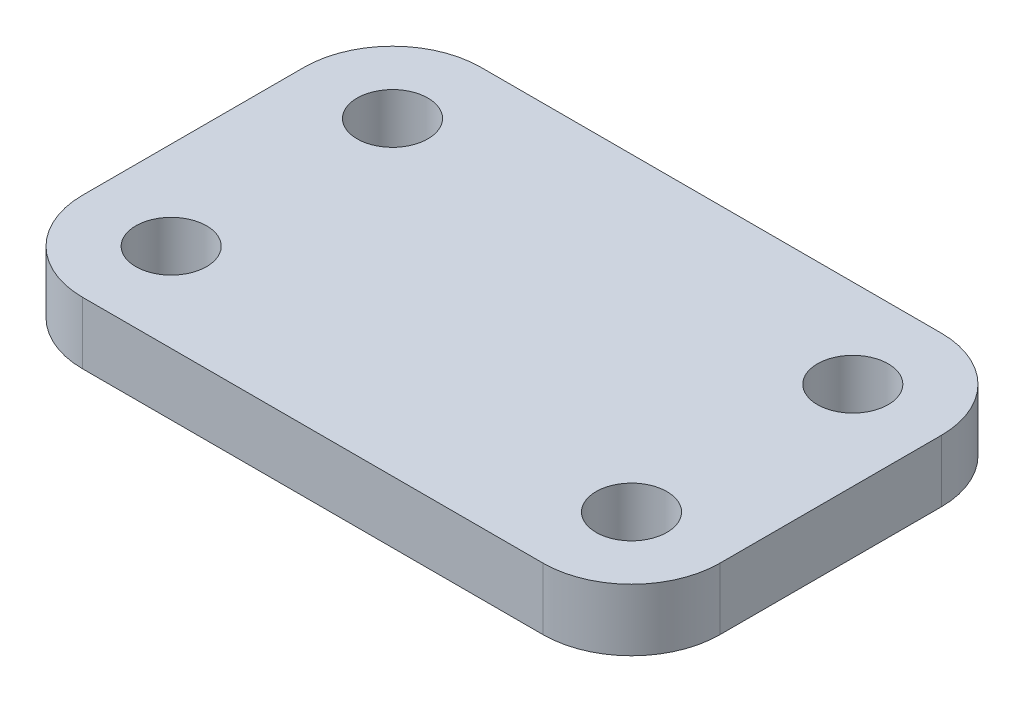
SolidWorks part; units mm, degrees
ref_plane "Alzado" through (0, 0, 0) normal (0, 0, 1) x (1, 0, 0)
ref_plane "Planta" through (0, 0, 0) normal (0, 1, 0) x (1, 0, 0)
ref_plane "Vista lateral" through (0, 0, 0) normal (1, 0, 0) x (0, 0, -1)
sketch "Croquis1" plane through (0, 0, 0) normal (0, 1, 0) x (1, 0, 0)
  line L1 (-35.0659, 31.7634) -> (16.9341, 31.7634)
  line L2 (-45.0659, 21.7634) -> (-45.0659, -3.2366)
  line L3 (-35.0659, -13.2366) -> (16.9341, -13.2366)
  line L4 (26.9341, 21.7634) -> (26.9341, -3.2366)
  arc A0 (-35.0659, 31.7634) -> (-45.0659, 21.7634) centre (-35.0659, 21.7634) ccw
  arc A1 (16.9341, 31.7634) -> (26.9341, 21.7634) centre (16.9341, 21.7634) cw
  arc A2 (16.9341, -13.2366) -> (26.9341, -3.2366) centre (16.9341, -3.2366) ccw
  arc A3 (-45.0659, -3.2366) -> (-35.0659, -13.2366) centre (-35.0659, -3.2366) ccw
  circle A4 centre (-35.0659, 21.7634) radius 4
  circle A5 centre (-35.0659, -3.2366) radius 4
  circle A6 centre (16.9341, 21.7634) radius 4
  circle A7 centre (16.9341, -3.2366) radius 4
  point P6 (-45.0659, 31.7634)
  point P9 (26.9341, 31.7634)
  point P12 (26.9341, -13.2366)
  point P19 (-35.0659, -7.6886)
  point P20 (0, 0)
  point P21 (0, 0)
  point P22 (0, 0)
  point P23 (0, 0)
  point P24 (0, 0)
  point P25 (0, 0)
  point P26 (0, 0)
  dimension "D3" = 10
  dimension "D4" = 10
  dimension "D5" = 8
  dimension "D6" = 8
  dimension "D7" = 8
  dimension "D8" = 8
  dimension "D1" = 72
  dimension "D2" = 45
extrude "Saliente-Extruir5" add sketch "Croquis1" along normal blind 7 contours L1 A1 L4 A2 L3 A3 L2 A0 | A4 | A5 | A7 | A6
